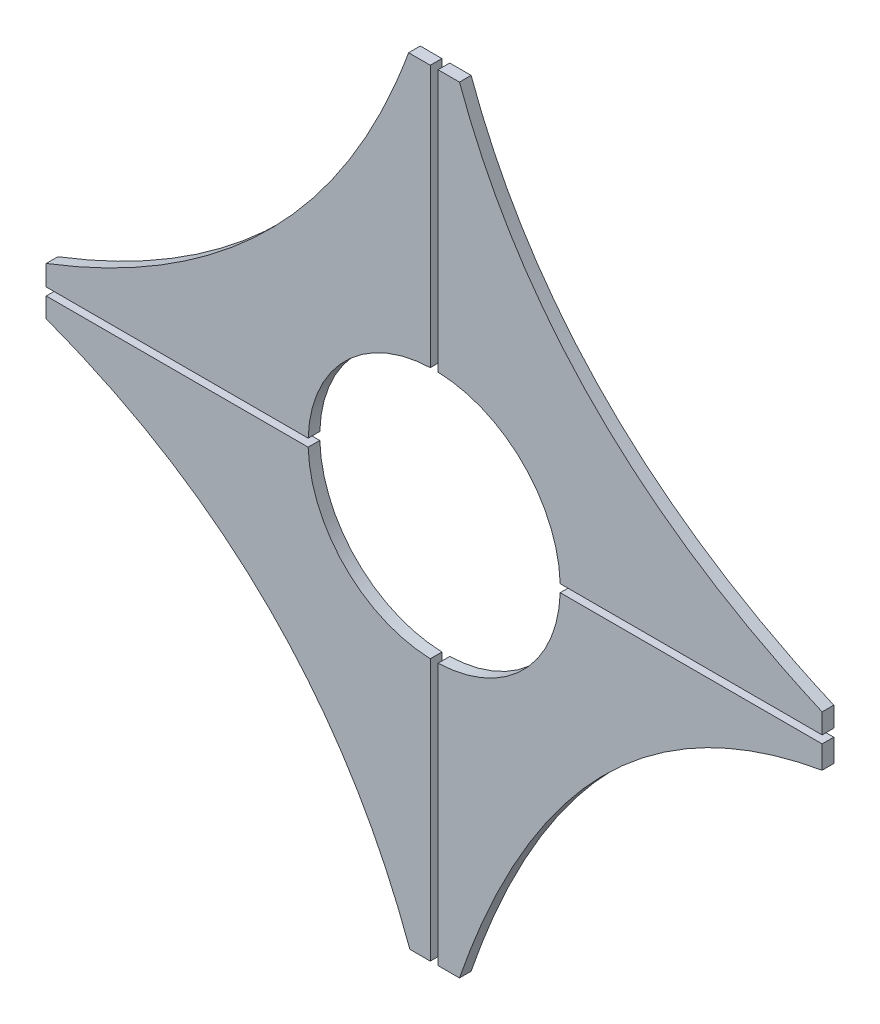
SolidWorks part; units mm, degrees
ref_plane "Plano frontal" through (0, 0, 0) normal (0, 0, 1) x (1, 0, 0)
ref_plane "Plano superior" through (0, 0, 0) normal (0, 1, 0) x (1, 0, 0)
ref_plane "Plano direito" through (0, 0, 0) normal (1, 0, 0) x (0, 0, -1)
sketch "Esboço2" plane through (0, 0, 0) normal (0, 0, 1) x (1, 0, 0)
  line L1 (-82.7093, 128.4747) -> (117.2907, 128.4747)
  line L2 (-82.7093, 128.4747) -> (-82.7093, -71.5253)
  line L3 (-82.7093, -71.5253) -> (117.2907, -71.5253)
  line L4 (117.2907, 128.4747) -> (117.2907, -71.5253)
extrude "Ressalto-extrusão1" add sketch "Esboço2" along normal blind 3 contours L2 L1 L4 L3
sketch "Esboço3" plane through (0, 0, 3) normal (0, 0, 1) x (1, 0, 0)
  line L1 (-82.7093, 128.4747) -> (117.2907, 128.4747) construction
  line L2 (117.2907, 128.4747) -> (117.2907, -71.5253) construction
  circle A1 centre (17.2907, 28.4747) radius 32.5
  dimension "D1" = 100
  dimension "D2" = 100
extrude "Corte-extrusão1" cut sketch "Esboço3" against normal blind 10
sketch "Esboço4" plane through (0, 0, 3) normal (0, 0, 1) x (1, 0, 0)
  line L0 (17.2907, 28.4747) -> (17.2907, 128.4747) construction
  line L1 (-82.7093, 128.4747) -> (117.2907, 128.4747) construction
  line L2 (-82.7093, 28.4747) -> (17.2907, 28.4747) construction
  line L3 (-82.7093, 128.4747) -> (-82.7093, -71.5253) construction
  line L4 (17.2907, 28.4747) -> (117.2907, 28.4747) construction
  line L5 (117.2907, 128.4747) -> (117.2907, -71.5253) construction
  line L6 (17.2907, 28.4747) -> (17.2907, -71.5253) construction
  line L7 (-82.7093, -71.5253) -> (117.2907, -71.5253) construction
  line L8 (17.2907, 53.3052) -> (16.2907, 53.3052)
  line L9 (16.2907, 53.3052) -> (16.2907, 128.4747)
  line L10 (16.2907, 128.4747) -> (18.2907, 128.4747)
  line L11 (18.2907, 128.4747) -> (18.2907, 53.3052)
  line L12 (18.2907, 53.3052) -> (17.2907, 53.3052)
  line L13 (38.803, 29.4747) -> (117.2907, 29.4747)
  line L14 (117.2907, 29.4747) -> (117.2907, 27.4747)
  line L15 (117.2907, 27.4747) -> (38.803, 27.4747)
  line L17 (38.803, 28.4747) -> (38.803, 29.4747)
  line L18 (38.803, 27.4747) -> (38.803, 28.4747)
  line L19 (18.2907, 6.0999) -> (18.2907, -71.5253)
  line L20 (18.2907, -71.5253) -> (16.2907, -71.5253)
  line L21 (16.2907, -71.5253) -> (16.2907, 6.0999)
  line L22 (16.2907, 6.0999) -> (18.2907, 6.0999)
  line L23 (-7.9245, 27.4747) -> (-82.7093, 27.4747)
  line L24 (-82.7093, 27.4747) -> (-82.7093, 28.4747)
  line L25 (-82.7093, 28.4747) -> (-82.7093, 29.4747)
  line L26 (-82.7093, 29.4747) -> (-7.9245, 29.4747)
  line L27 (-7.9245, 29.4747) -> (-7.9245, 27.4747)
  dimension "D1" = 2
  dimension "D2" = 1
  dimension "D3" = 1
  dimension "D4" = 2
extrude "Corte-extrusão2" cut sketch "Esboço4" against normal blind 10
sketch "Esboço5" plane through (0, 0, 3) normal (0, 0, 1) x (1, 0, 0)
  line L0 (18.2907, 128.4747) -> (117.2907, 128.4747) construction
  line L1 (117.2907, 128.4747) -> (117.2907, 29.4747) construction
  line L2 (23.8098, 128.4747) -> (117.2907, 128.4747)
  line L3 (117.2907, 128.4747) -> (117.2907, 34.6247)
  spline S0 degree 2 poles (23.8098, 128.4747) (46.7456, 65.4589) (117.2907, 34.6247) knots 0 0 0 1 1 1
extrude "Corte-extrusão3" cut sketch "Esboço5" against normal blind 10
sketch "Esboço6" plane through (0, 0, 3) normal (0, 0, 1) x (1, 0, 0)
  line L0 (-82.7093, 128.4747) -> (-82.7093, 29.4747) construction
  line L1 (-82.7093, 128.4747) -> (16.2907, 128.4747) construction
  line L2 (-82.7093, 34.7306) -> (-82.7093, 128.4747)
  line L3 (-82.7093, 128.4747) -> (10.7018, 128.4747)
  spline S0 degree 2 poles (-82.7093, 34.7306) (-13.8046, 61.144) (10.7018, 128.4747) knots 0 0 0 1 1 1
extrude "Corte-extrusão4" cut sketch "Esboço6" against normal blind 10
sketch "Esboço7" plane through (0, 0, 3) normal (0, 0, 1) x (1, 0, 0)
  line L0 (117.2907, 27.4747) -> (117.2907, -71.5253) construction
  line L1 (18.2907, -71.5253) -> (117.2907, -71.5253) construction
  line L2 (23.8098, -71.5253) -> (117.2907, -71.5253)
  line L3 (117.2907, -71.5253) -> (117.2907, 21.5866)
  spline S0 degree 2 poles (117.2907, 21.5866) (51.8517, 10.048) (23.8098, -71.5253) knots 0 0 0 1 1 1
extrude "Corte-extrusão5" cut sketch "Esboço7" against normal blind 10
sketch "Esboço8" plane through (0, 0, 3) normal (0, 0, 1) x (1, 0, 0)
  line L0 (-82.7093, 27.4747) -> (-82.7093, -71.5253) construction
  line L1 (-82.7093, -71.5253) -> (16.2907, -71.5253) construction
  line L2 (-82.7093, 22.3246) -> (-82.7093, -71.5253)
  line L3 (-82.7093, -71.5253) -> (11.0177, -71.5253)
  spline S0 degree 2 poles (-82.7093, 22.3246) (-13.8242, -3.2728) (11.0177, -71.5253) knots 0 0 0 1 1 1
  point P2 (-82.7093, 22.3246)
extrude "Corte-extrusão6" cut sketch "Esboço8" against normal blind 10
